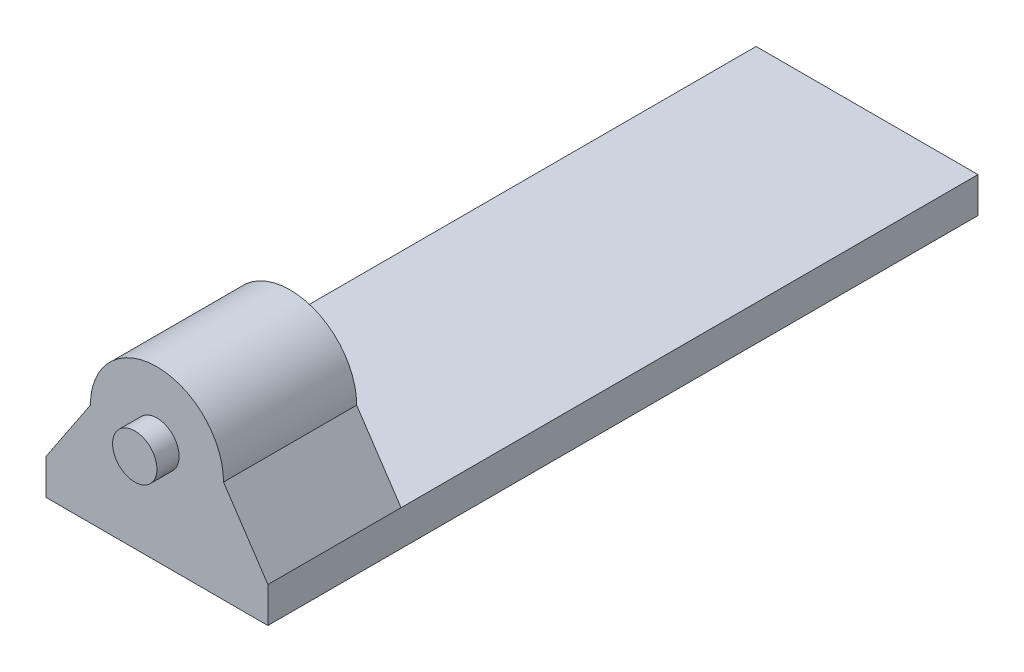
SolidWorks part; units mm, degrees
ref_plane "前视基准面" through (0, 0, 0) normal (0, 0, 1) x (1, 0, 0)
ref_plane "上视基准面" through (0, 0, 0) normal (0, 1, 0) x (1, 0, 0)
ref_plane "右视基准面" through (0, 0, 0) normal (1, 0, 0) x (0, 0, -1)
sketch "草图1" plane through (0, 0, 0) normal (0, 0, 1) x (1, 0, 0)
  line L0 (-39.8017, 0) -> (0, 0) construction
  line L1 (0, 0) -> (0, 40.2975) construction
  line L3 (-25, 4) -> (25, 4)
  line L4 (-25, 4) -> (-25, -4)
  line L5 (-25, -4) -> (25, -4)
  line L6 (25, 4) -> (25, -4)
  dimension "D1" = 50
  dimension "D2" = 25
  dimension "D3" = 8
  dimension "D4" = 4
sketch "草图2" plane through (0, 0, 0) normal (1, 0, 0) x (0, 0, -1)
  line L0 (0, 55.2983) -> (-160, 55.2983)
  line L1 (0, 4) -> (0, -4) construction
  line L2 (0, 4) -> (0, -4) construction
sweep "扫描1" add profiles "草图1" path "草图2"
sketch "草图4" plane through (0, 0, 160) normal (0, 0, 1) x (1, 0, 0)
  line L0 (-25, 4) -> (25, 4) construction
  line L1 (15, 19) -> (25, 4)
  line L2 (25, 4) -> (-25, 4)
  line L3 (-25, 4) -> (-15, 19)
  arc A0 (15, 19) -> (-15, 19) centre (0, 19) ccw
  dimension "D1" = 15
extrude "凸台-拉伸2" add sketch "草图4" against normal blind 30
sketch "草图5" plane through (0, 0, 160) normal (0, 0, 1) x (1, 0, 0)
  circle A0 centre (0, 19) radius 5
extrude "凸台-拉伸3" add sketch "草图5" along normal blind 5
